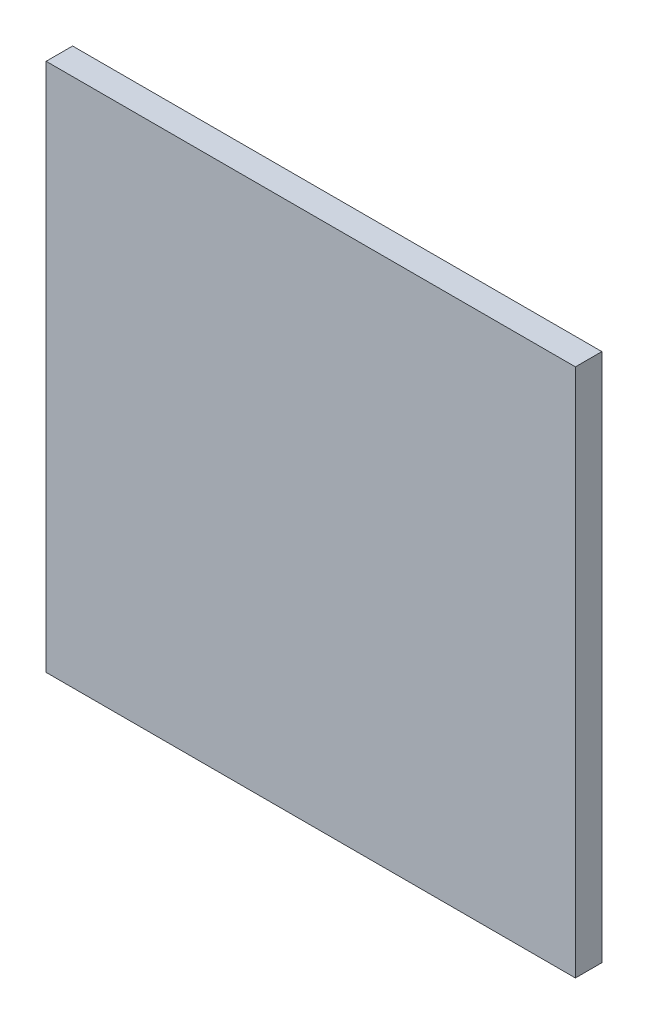
SolidWorks part; units mm, degrees
ref_plane "Front" through (0, 0, 0) normal (0, 0, 1) x (1, 0, 0)
ref_plane "Top" through (0, 0, 0) normal (0, 1, 0) x (1, 0, 0)
ref_plane "Right" through (0, 0, 0) normal (1, 0, 0) x (0, 0, -1)
other "Configuration Table"
sketch "Sketch1" plane through (0, 0, 0) normal (0, 0, 1) x (1, 0, 0)
  line L1 (0, 0) -> (508, 0)
  line L2 (0, 0) -> (0, 508)
  line L3 (0, 508) -> (508, 508)
  line L4 (508, 0) -> (508, 508)
  dimension "D1" = 508
  dimension "D2" = 508
extrude "Extrude1" add sketch "Sketch1" against normal blind 25.4
